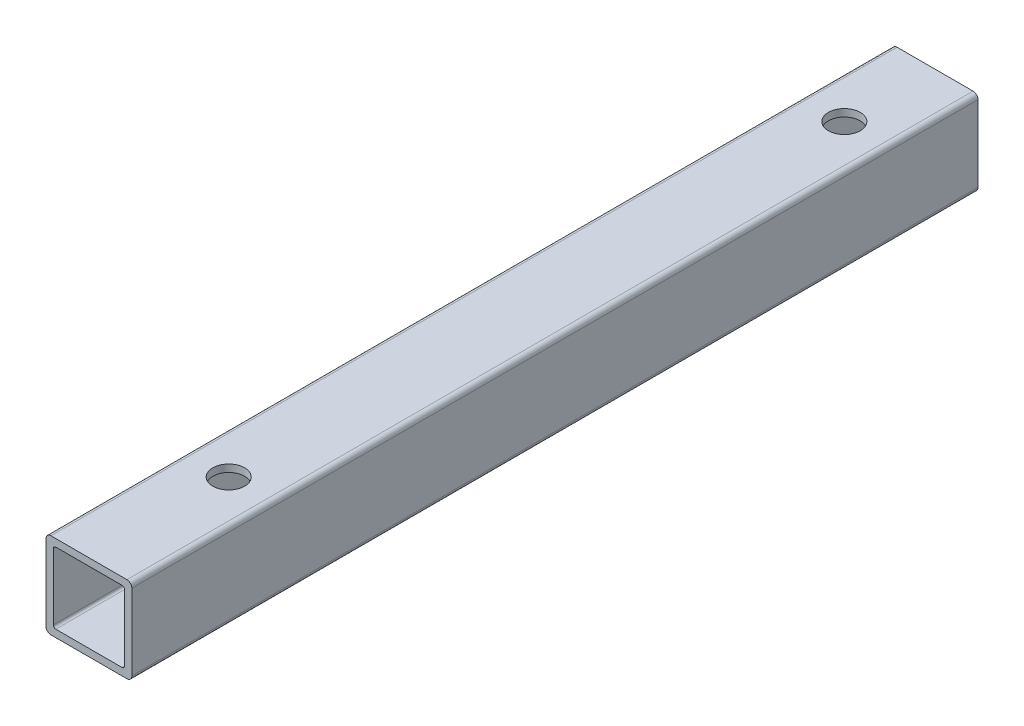
SolidWorks part; units mm, degrees
material "1.0553 (S355J0)"
ref_plane "Płaszczyzna przednia" through (0, 0, 0) normal (0, 0, 1) x (1, 0, 0)
ref_plane "Płaszczyzna górna" through (0, 0, 0) normal (0, 1, 0) x (1, 0, 0)
ref_plane "Płaszczyzna prawa" through (0, 0, 0) normal (1, 0, 0) x (0, 0, -1)
sketch "Szkic1" plane through (0, 0, 0) normal (0, 0, 1) x (1, 0, 0)
  line L1 (2, 0) -> (33, 0)
  line L2 (0, 2) -> (0, 33)
  line L3 (2, 35) -> (33, 35)
  line L4 (35, 2) -> (35, 33)
  line L5 (4, 3) -> (31, 3)
  line L6 (3, 4) -> (3, 31)
  line L7 (4, 32) -> (31, 32)
  line L8 (32, 4) -> (32, 31)
  arc A0 (33, 0) -> (35, 2) centre (33, 2) ccw
  arc A1 (35, 33) -> (33, 35) centre (33, 33) ccw
  arc A2 (2, 35) -> (0, 33) centre (2, 33) ccw
  arc A3 (0, 2) -> (2, 0) centre (2, 2) ccw
  arc A4 (3, 4) -> (4, 3) centre (4, 4) ccw
  arc A5 (31, 3) -> (32, 4) centre (31, 4) ccw
  arc A6 (32, 31) -> (31, 32) centre (31, 31) ccw
  arc A7 (4, 32) -> (3, 31) centre (4, 31) ccw
  point P7 (35, 0)
  point P12 (0, 35)
  point P15 (0, 0)
  dimension "D3" = 2
  dimension "D8" = 1
  dimension "D1" = 35
  dimension "D2" = 35
  dimension "D4" = 3
  dimension "D5" = 3
  dimension "D6" = 3
  dimension "D7" = 3
extrude "Dodanie-wyciągnięcie1" add sketch "Szkic1" along normal blind 345
sketch "Szkic2" plane through (0, 35, 0) normal (0, 1, 0) x (1, 0, 0)
  line L0 (17.5, -345) -> (17.5, 0) construction
  line L1 (33, -345) -> (2, -345) construction
  line L2 (-19.25, 0) -> (19.25, 0) construction
  circle A0 centre (17.5, -288) radius 6.5
  circle A1 centre (17.5, -37) radius 6.5
  dimension "D3" = 13
  dimension "D1" = 57
  dimension "D2" = 37
extrude "Wytnij-wyciągnięcie1" cut sketch "Szkic2" against normal blind 345
